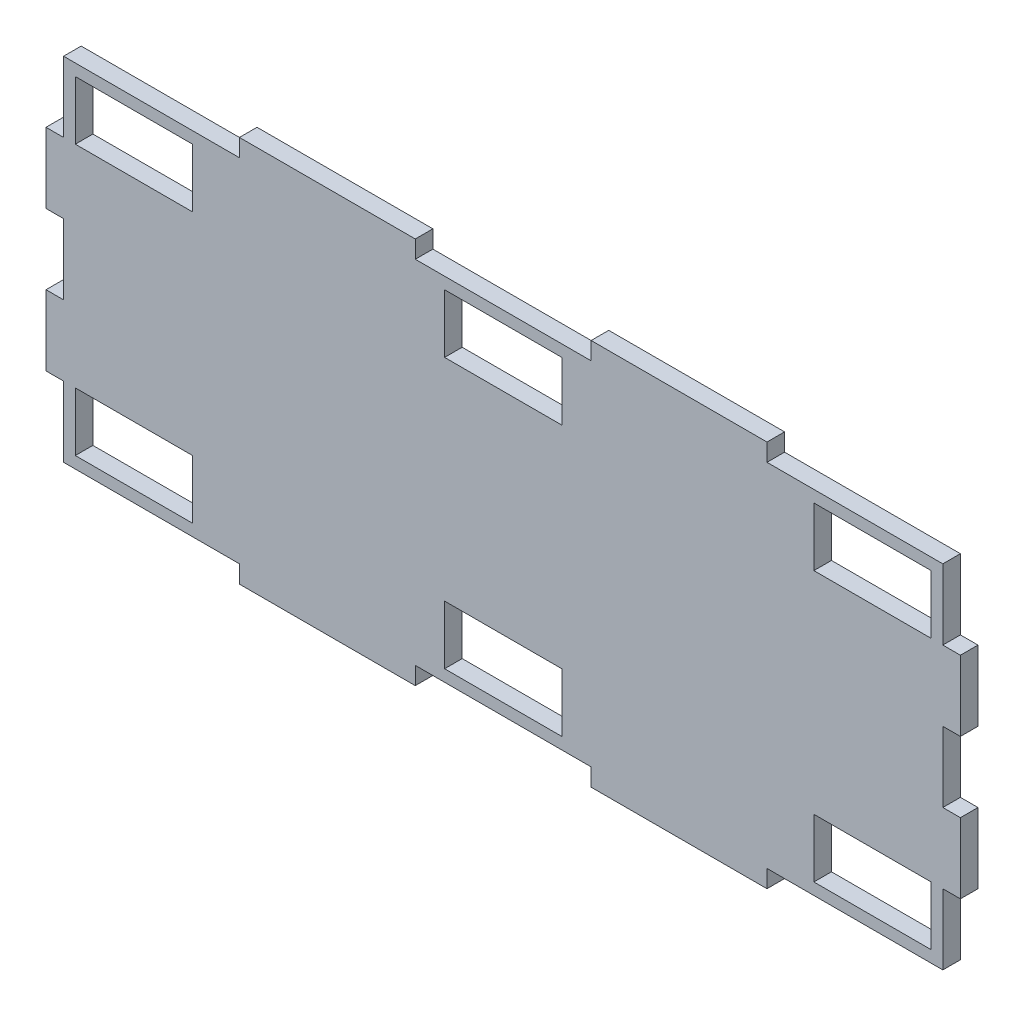
SolidWorks part; units mm, degrees
material "Pinho"
ref_plane "Plano frontal" through (0, 0, 0) normal (0, 0, 1) x (1, 0, 0)
ref_plane "Plano superior" through (0, 0, 0) normal (0, 1, 0) x (1, 0, 0)
ref_plane "Plano direito" through (0, 0, 0) normal (1, 0, 0) x (0, 0, -1)
sketch "Esboço1" plane through (0, 0, 0) normal (0, 0, 1) x (1, 0, 0)
  line L0 (-15, 30) -> (15, 30)
  line L1 (-75, -30) -> (-45, -30)
  line L2 (-75, -30) -> (-75, -18)
  line L3 (-75, 30) -> (-45, 30)
  line L4 (75, -30) -> (75, -18)
  line L5 (-75, -30) -> (75, 30) construction
  line L6 (-75, 30) -> (75, -30) construction
  line L8 (-45, 30) -> (-45, 33)
  line L9 (-45, 33) -> (-15, 33)
  line L10 (-15, 30) -> (-15, 33)
  line L11 (-15, -30) -> (15, -30)
  line L14 (15, 30) -> (15, 33)
  line L15 (15, 33) -> (45, 33)
  line L16 (45, 30) -> (45, 33)
  line L17 (-45, -30) -> (-45, -33)
  line L18 (-45, -33) -> (-15, -33)
  line L19 (45, 30) -> (75, 30)
  line L20 (-15, -30) -> (-15, -33)
  line L21 (45, -30) -> (75, -30)
  line L22 (75, 18) -> (75, 30)
  line L24 (15, -30) -> (15, -33)
  line L25 (15, -33) -> (45, -33)
  line L26 (45, -30) -> (45, -33)
  line L27 (-75, 18) -> (-78, 18)
  line L29 (-75, 6) -> (-78, 6)
  line L30 (-78, 18) -> (-78, 6)
  line L32 (73, -18) -> (53, -18)
  line L33 (-75, -6) -> (-78, -6)
  line L35 (-75, -18) -> (-78, -18)
  line L36 (-78, -6) -> (-78, -18)
  line L37 (-75, 18) -> (-75, 30)
  line L38 (73, -18) -> (73, -28)
  line L39 (75, 6) -> (78, 6)
  line L41 (75, 18) -> (78, 18)
  line L42 (78, 6) -> (78, 18)
  line L43 (75, -6) -> (75, 6)
  line L44 (-75, -6) -> (-75, 6)
  line L45 (75, -18) -> (78, -18)
  line L47 (75, -6) -> (78, -6)
  line L48 (78, -18) -> (78, -6)
  line L49 (73, -28) -> (53, -28)
  line L50 (53, -18) -> (53, -28)
  line L51 (73, -18) -> (53, -28) construction
  line L52 (73, -28) -> (53, -18) construction
  line L53 (-73, -18) -> (-53, -18)
  line L54 (-73, -18) -> (-73, -28)
  line L55 (-73, -28) -> (-53, -28)
  line L56 (-53, -18) -> (-53, -28)
  line L57 (-73, -18) -> (-53, -28) construction
  line L58 (-73, -28) -> (-53, -18) construction
  line L59 (-73, 18) -> (-53, 18)
  line L60 (-73, 18) -> (-73, 28)
  line L61 (-73, 28) -> (-53, 28)
  line L62 (-53, 18) -> (-53, 28)
  line L63 (-73, 18) -> (-53, 28) construction
  line L64 (-73, 28) -> (-53, 18) construction
  line L65 (73, 28) -> (53, 28)
  line L66 (73, 28) -> (73, 18)
  line L67 (73, 18) -> (53, 18)
  line L68 (53, 28) -> (53, 18)
  line L69 (73, 28) -> (53, 18) construction
  line L70 (73, 18) -> (53, 28) construction
  line L71 (10, -28) -> (-10, -28)
  line L72 (10, -28) -> (10, -18)
  line L73 (10, -18) -> (-10, -18)
  line L74 (-10, -28) -> (-10, -18)
  line L75 (10, -28) -> (-10, -18) construction
  line L76 (10, -18) -> (-10, -28) construction
  line L77 (10, 18) -> (-10, 18)
  line L78 (10, 18) -> (10, 28)
  line L79 (10, 28) -> (-10, 28)
  line L80 (-10, 18) -> (-10, 28)
  line L81 (10, 18) -> (-10, 28) construction
  line L82 (10, 28) -> (-10, 18) construction
  point P0 (0, 0)
  point P6 (-63, -23)
  point P32 (63, -23)
  point P48 (-63, 23)
  point P53 (63, 23)
  point P58 (0, 23)
  point P59 (0, -23)
  dimension "D1" = 150
  dimension "D2" = 60
  dimension "D3" = 30
  dimension "D4" = 30
  dimension "D5" = 30
  dimension "D6" = 30
  dimension "D7" = 3
  dimension "D8" = 3
  dimension "D9" = 30
  dimension "D10" = 30
  dimension "D11" = 30
  dimension "D12" = 30
  dimension "D13" = 3
  dimension "D14" = 3
  dimension "D15" = 12
  dimension "D16" = 12
  dimension "D17" = 12
  dimension "D18" = 12
  dimension "D19" = 12
  dimension "D20" = 12
  dimension "D21" = 12
  dimension "D22" = 12
  dimension "D23" = 3
  dimension "D24" = 3
  dimension "D25" = 3
  dimension "D26" = 3
  dimension "D27" = 10
  dimension "D28" = 20
  dimension "D29" = 20
  dimension "D30" = 10
  dimension "D31" = 20
  dimension "D32" = 10
  dimension "D33" = 20
  dimension "D34" = 10
  dimension "D35" = 2
  dimension "D36" = 2
  dimension "D37" = 2
  dimension "D38" = 2
  dimension "D39" = 2
  dimension "D40" = 2
  dimension "D41" = 2
  dimension "D42" = 2
  dimension "D43" = 10
  dimension "D44" = 20
  dimension "D45" = 20
  dimension "D46" = 10
  dimension "D47" = 5
  dimension "D48" = 5
  dimension "D49" = 2
  dimension "D50" = 2
extrude "Ressalto-extrusão1" add sketch "Esboço1" along normal blind 3
